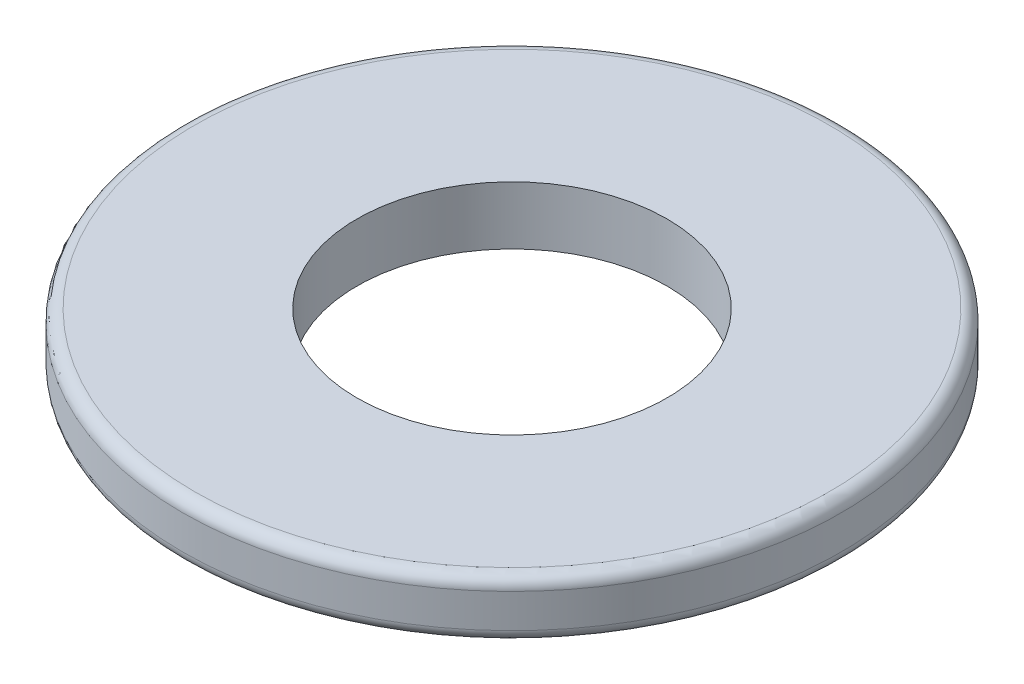
SolidWorks part; units mm, degrees
ref_plane "Front Plane" through (0, 0, 0) normal (0, 0, 1) x (1, 0, 0)
ref_plane "Top Plane" through (0, 0, 0) normal (0, 1, 0) x (1, 0, 0)
ref_plane "Right Plane" through (0, 0, 0) normal (1, 0, 0) x (0, 0, -1)
sketch "Sketch1" plane through (0, 0, 0) normal (0, 1, 0) x (1, 0, 0)
  circle A0 centre (0, 0) radius 3.4
  circle A1 centre (0, 0) radius 1.6
  dimension "D1" = 6.8
  dimension "D2" = 3.2
extrude "Boss-Extrude1" add sketch "Sketch1" along normal blind 0.6
fillet "Fillet1" radius 0.125 2 edges at (0, 0, 3.4) (0, 0.6, 3.4)
